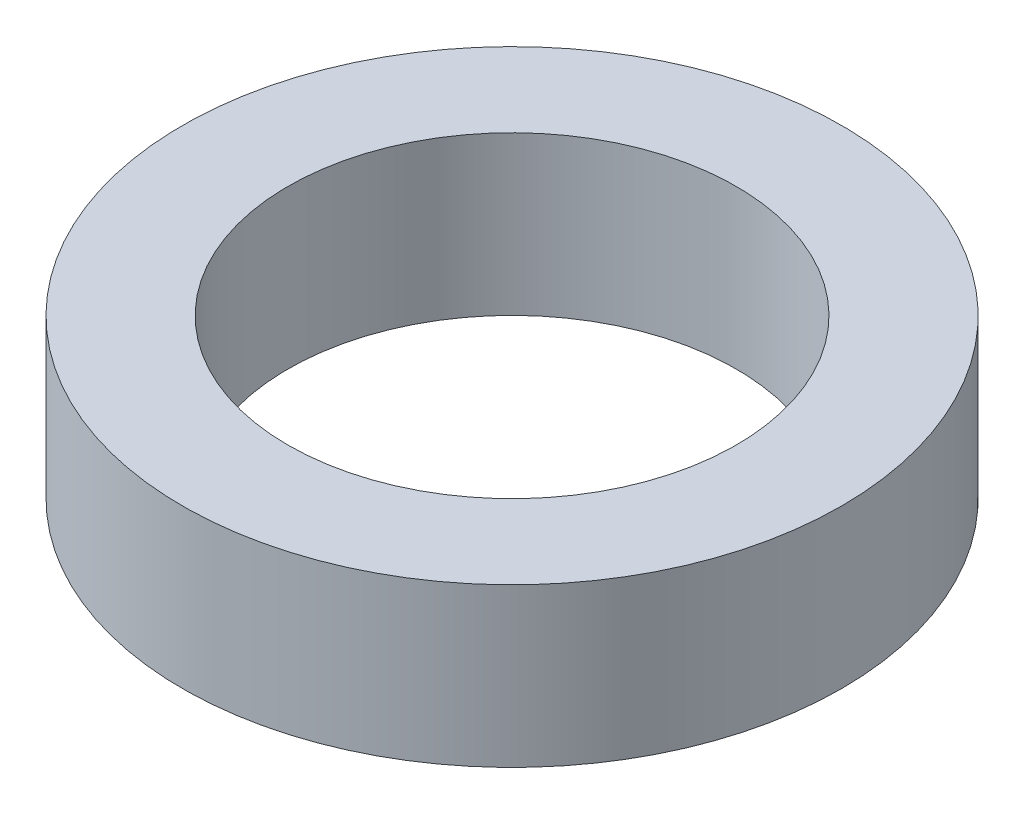
SolidWorks part; units mm, degrees
ref_plane "Front Plane" through (0, 0, 0) normal (0, 0, 1) x (1, 0, 0)
ref_plane "Top Plane" through (0, 0, 0) normal (0, 1, 0) x (1, 0, 0)
ref_plane "Right Plane" through (0, 0, 0) normal (1, 0, 0) x (0, 0, -1)
sketch "Sketch1" plane through (0, 0, 0) normal (0, 1, 0) x (1, 0, 0)
  circle A0 centre (0, 0) radius 4.25
  dimension "D1" = 8.5
extrude "Extrude-Thin1" add sketch "Sketch1" along normal blind 3 thin contours A0
